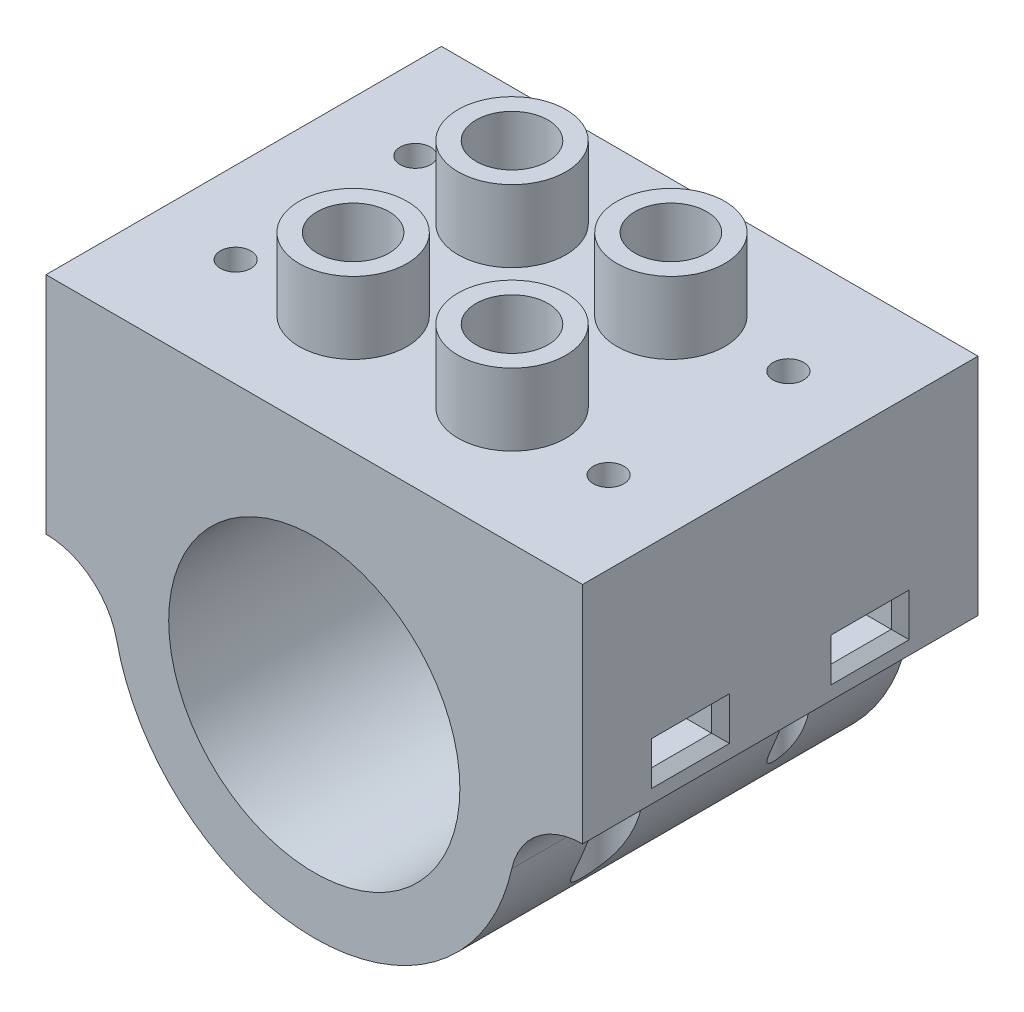
SolidWorks part; units mm, degrees
ref_plane "Front Plane" through (0, 0, 0) normal (0, 0, 1) x (1, 0, 0)
ref_plane "Top Plane" through (0, 0, 0) normal (0, 1, 0) x (1, 0, 0)
ref_plane "Right Plane" through (0, 0, 0) normal (1, 0, 0) x (0, 0, -1)
sketch "Sketch1" plane through (0, 0, 0) normal (0, 0, 1) x (1, 0, 0)
  line L0 (0, -1000) -> (0, 49000) construction
  line L1 (-29.85, 1.5) -> (29.85, 1.5)
  line L2 (-29.85, 1.5) -> (-29.85, 26.5)
  line L3 (-29.85, 26.5) -> (29.85, 26.5)
  line L4 (29.85, 1.5) -> (29.85, 26.5)
  line L5 (-29.85, 1.5) -> (29.85, 26.5) construction
  line L6 (-29.85, 26.5) -> (29.85, 1.5) construction
  circle A0 centre (0, 0) radius 16.2 construction
  circle A1 centre (0, 0) radius 22.5
  arc A2 (21.9751, -4.8316) -> (29.85, 1.5) centre (29.85, -6.563) cw
  arc A3 (-21.9751, -4.8316) -> (-29.85, 1.5) centre (-29.85, -6.563) ccw
  point P15 (0, 14)
  dimension "D1" = 32.4
  dimension "D5" = 45
  dimension "D2" = 25
  dimension "D3" = 59.7
  dimension "D4" = 14
extrude "Boss-Extrude1" add sketch "Sketch1" along normal blind 44 contours A1 L3 L2 L1 | L3 A1 L1 | A1 L1 L4 L3 | A3 A1 L1 | L1 A1 | A1 A2 L1
sketch "Sketch2" plane through (0, 0, 44) normal (0, 0, 1) x (1, 0, 0)
  circle A0 centre (0, 0) radius 16.2
  dimension "D1" = 32.4
extrude "Cut-Extrude1" cut sketch "Sketch2" against normal blind 35
sketch "Sketch3" plane through (0, 0, 0) normal (0, 0, -1) x (-1, 0, 0)
  circle A0 centre (0, 0) radius 9.7
  dimension "D1" = 19.4
extrude "Cut-Extrude2" cut sketch "Sketch3" against normal up to next
sketch "Sketch4" plane through (0, 0, 0) normal (0, 0, -1) x (-1, 0, 0)
  line L0 (0, -1000) -> (0, 49000) construction
  line L1 (-4.4463, 12.216) -> (0, 0) construction
  line L2 (0, 0) -> (-4.4463, 12.216) construction
  circle A0 centre (0, 0) radius 13 construction
  point P3 (-4.4463, 12.216)
  point P7 (12.216, 4.4463)
  point P10 (4.4463, -12.216)
  point P11 (-12.216, -4.4463)
  dimension "D1" = 26
  dimension "D2" = 20
  dimension "D4" = 13
  dimension "D3" = 4
hole_wizard "CBORE for M3 SHCS1" positions "Sketch4" profile "Sketch5" counterbore size "M3" standard "ANSI Metric" end condition through all
sketch "Sketch5" plane through (12.216, -4.4463, 0) normal (1, 0, 0) x (0, 1, 0)
  line L0 (0, 0) -> (0, 44)
  line L1 (0, 44) -> (1.7, 44)
  line L3 (1.7, 44) -> (1.7, 3)
  line L4 (1.7, 3) -> (3.25, 3)
  line L5 (3.25, 3) -> (3.25, 0)
  line L7 (3.25, 0) -> (0, 0)
  line L11 (0, -6.35) -> (0, 107.95) construction
  dimension "Thru Hole Dia." = 3.4
  dimension "Thru Hole Depth" = 44
  dimension "C'Bore Dia." = 6.5
  dimension "C'Bore Depth" = 3
sketch "Sketch6" plane through (0, 26.5, 0) normal (0, 1, 0) x (1, 0, 0)
  line L0 (0, -1000) -> (0, 49000) construction
  line L1 (-29.85, 0) -> (29.85, 0) construction
  line L2 (-1000, 24000) -> (49000, 24000) construction
  line L3 (-970.15, -22) -> (49029.85, -22) construction
  line L4 (29.85, -44) -> (29.85, 0) construction
  circle A0 centre (20.75, -12) radius 1.7
  circle A1 centre (20.75, -32) radius 1.7
  circle A2 centre (-20.75, -12) radius 1.7
  circle A3 centre (-20.75, -32) radius 1.7
  point P8 (0, 24000)
  point P15 (29.85, -22)
  dimension "D1" = 3.4
  dimension "D2" = 41.5
  dimension "D3" = 12
extrude "Cut-Extrude3" cut sketch "Sketch6" against normal up to next
ref_plane "Plane1" through (0, 1.5, 0) normal (0, -1, 0) x (-1, 0, 0)
ref_plane "Plane2" through (0, 14, 0) normal (0, -1, 0) x (-1, 0, 0)
ref_plane "Plane4" through (0, 4, 0) normal (0, -1, 0) x (-1, 0, 0)
sketch "Sketch7" plane through (0, 4, 0) normal (0, -1, 0) x (-1, 0, 0)
  line L0 (20.75, -8.6514) -> (29.85, -8.6514)
  line L1 (20.75, -8.6514) -> (17.85, -10.3257)
  line L2 (17.85, -10.3257) -> (17.85, -13.6743)
  line L3 (17.85, -13.6743) -> (20.75, -15.3486)
  line L4 (20.75, -15.3486) -> (23.65, -13.6743)
  line L5 (23.65, -13.6743) -> (23.65, -10.3257)
  line L6 (23.65, -10.3257) -> (20.75, -8.6514)
  line L7 (29.85, -44) -> (29.85, 0) construction
  line L8 (29.85, -8.6514) -> (29.85, -15.3486)
  line L9 (29.85, -15.3486) -> (20.75, -15.3486)
  line L10 (0, 0) -> (0, -44) construction
  line L11 (21.9751, 0) -> (-21.9751, 0) construction
  line L12 (-21.9751, -44) -> (21.9751, -44) construction
  line L13 (29.85, -22) -> (-29.85, -22) construction
  line L14 (-29.85, -44) -> (-29.85, 0) construction
  line L15 (29.85, -28.6514) -> (20.75, -28.6514)
  line L16 (29.85, -35.3486) -> (29.85, -28.6514)
  line L17 (23.65, -33.6743) -> (20.75, -35.3486)
  line L18 (23.65, -30.3257) -> (23.65, -33.6743)
  line L19 (20.75, -28.6514) -> (23.65, -30.3257)
  line L20 (17.85, -30.3257) -> (20.75, -28.6514)
  line L21 (17.85, -33.6743) -> (17.85, -30.3257)
  line L22 (20.75, -35.3486) -> (17.85, -33.6743)
  line L23 (20.75, -35.3486) -> (29.85, -35.3486)
  line L24 (-20.75, -35.3486) -> (-29.85, -35.3486)
  line L25 (-20.75, -35.3486) -> (-17.85, -33.6743)
  line L26 (-17.85, -33.6743) -> (-17.85, -30.3257)
  line L27 (-17.85, -30.3257) -> (-20.75, -28.6514)
  line L28 (-20.75, -28.6514) -> (-23.65, -30.3257)
  line L29 (-23.65, -30.3257) -> (-23.65, -33.6743)
  line L30 (-23.65, -33.6743) -> (-20.75, -35.3486)
  line L31 (-29.85, -35.3486) -> (-29.85, -28.6514)
  line L32 (-29.85, -28.6514) -> (-20.75, -28.6514)
  line L33 (-29.85, -15.3486) -> (-20.75, -15.3486)
  line L34 (-29.85, -8.6514) -> (-29.85, -15.3486)
  line L35 (-23.65, -10.3257) -> (-20.75, -8.6514)
  line L36 (-23.65, -13.6743) -> (-23.65, -10.3257)
  line L37 (-20.75, -15.3486) -> (-23.65, -13.6743)
  line L38 (-17.85, -13.6743) -> (-20.75, -15.3486)
  line L39 (-17.85, -10.3257) -> (-17.85, -13.6743)
  line L40 (-20.75, -8.6514) -> (-17.85, -10.3257)
  line L41 (-20.75, -8.6514) -> (-29.85, -8.6514)
  circle A0 centre (20.75, -12) radius 2.9 construction
  circle A1 centre (20.75, -32) radius 2.9 construction
  circle A2 centre (-20.75, -32) radius 2.9 construction
  circle A3 centre (-20.75, -12) radius 2.9 construction
  dimension "D1" = 5.8
extrude "Cut-Extrude4" cut sketch "Sketch7" against normal blind 2.8 contours L35 L41 L34 L33 L37 L36 | L32 L31 L24 L30 L29 L28 | L29 L30 L25 L26 L27 L28 | L40 L35 L36 L37 L38 L39 | L9 L8 L0 L6 L5 L4 | L5 L6 L1 L2 L3 L4 | L17 L23 L16 L15 L19 L18 | L22 L17 L18 L19 L20 L21
chamfer "Chamfer1" distance 1 angle 45 16 edges at (29.85, 5.4, 35.3486) (29.85, 4, 32) (29.85, 5.4, 28.6514) (29.85, 6.8, 32) (29.85, 5.4, 15.3486) (29.85, 4, 12) (29.85, 5.4, 8.6514) (29.85, 6.8, 12) (-29.85, 4, 32) (-29.85, 5.4, 35.3486) (-29.85, 6.8, 32) (-29.85, 5.4, 28.6514) (-29.85, 4, 12) (-29.85, 5.4, 15.3486) (-29.85, 6.8, 12) (-29.85, 5.4, 8.6514)
ref_plane "Plane3" through (0, -18.5, 0) normal (0, -1, 0) x (-1, 0, 0)
sketch "Sketch8" plane through (0, -18.5, 0) normal (0, -1, 0) x (-1, 0, 0)
  circle A1 centre (20.75, -32) radius 3
  circle A3 centre (-20.75, -32) radius 3
  dimension "D1" = 6
extrude "Cut-Extrude5" cut sketch "Sketch8" against normal offset from surface (12.5 mm away) 10 up to face at (-22.4833, 4, 12)
sketch "Sketch9" plane through (0, 26.5, 0) normal (0, 1, 0) x (1, 0, 0)
  line L0 (-29.85, -22) -> (29.85, -22) construction
  line L1 (-29.85, -44) -> (-29.85, 0) construction
  line L2 (29.85, -44) -> (29.85, 0) construction
  line L3 (0, 0) -> (0, -44) construction
  line L4 (-29.85, 0) -> (29.85, 0) construction
  line L5 (-29.85, -44) -> (29.85, -44) construction
  line L6 (0, -22) -> (8.8388, -13.1612) construction
  circle A0 centre (0, -22) radius 12.5 construction
  circle A1 centre (8.8388, -13.1612) radius 4
  circle A2 centre (8.8388, -30.8388) radius 4
  circle A3 centre (-8.8388, -30.8388) radius 4
  circle A4 centre (-8.8388, -13.1612) radius 4
  dimension "D1" = 25
  dimension "D2" = 8
  dimension "D3" = 45
  dimension "D4" = 4
extrude "Cut-Extrude6" cut sketch "Sketch9" against normal blind 9
sketch "Sketch10" plane through (0, 26.5, 0) normal (0, 1, 0) x (1, 0, 0)
  circle A0 centre (-8.8388, -13.1612) radius 4 construction
  circle A1 centre (8.8388, -30.8388) radius 4 construction
  circle A2 centre (-8.8388, -30.8388) radius 4 construction
  circle A3 centre (8.8388, -13.1612) radius 4 construction
  circle A4 centre (-8.8388, -13.1612) radius 4
  circle A5 centre (8.8388, -30.8388) radius 4
  circle A6 centre (-8.8388, -30.8388) radius 4
  circle A7 centre (8.8388, -13.1612) radius 4
  circle A8 centre (8.8388, -13.1612) radius 6
  circle A9 centre (8.8388, -30.8388) radius 6
  circle A10 centre (-8.8388, -30.8388) radius 6
  circle A11 centre (-8.8388, -13.1612) radius 6
  dimension "D1" = 2
  dimension "D2" = 2
  dimension "D3" = 2
  dimension "D4" = 2
extrude "Boss-Extrude2" add sketch "Sketch10" along normal blind 8
sketch "Sketch11" plane through (-29.85, 0, 0) normal (-1, 0, 0) x (0, 0, 1)
  line L0 (44, 26.5) -> (0, 26.5) construction
  line L1 (22, 18) -> (22, 10) construction
  line L2 (-24.2, 14) -> (24.2, 14) construction
  circle A0 centre (22, 10) radius 2.275
  circle A1 centre (22, 18) radius 2.275
  point P6 (22, 26.5)
  point P9 (22, 14)
  dimension "D1" = 4.55
  dimension "D2" = 8
extrude "Cut-Extrude7" cut sketch "Sketch11" against normal blind 8
chamfer "Chamfer2" distance 0.75 angle 45 2 edges at (-29.85, 10, 24.275) (-29.85, 18, 24.275)
equation "\"spring_OD\"= 6mm"
equation "\"D1@Sketch8\"=\"spring_OD\""
